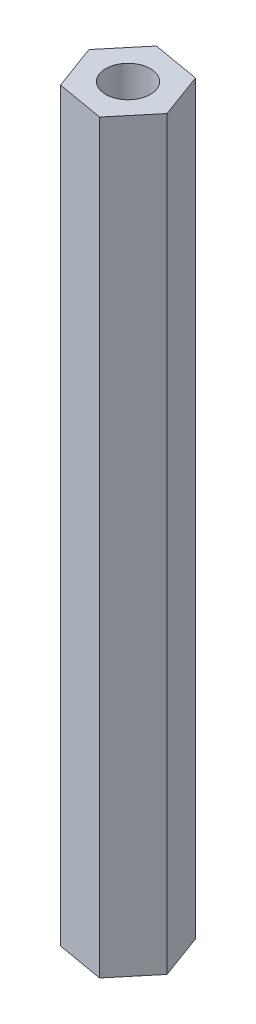
SolidWorks part; units mm, degrees
ref_plane "Front Plane" through (0, 0, 0) normal (0, 0, 1) x (1, 0, 0)
ref_plane "Top Plane" through (0, 0, 0) normal (0, 1, 0) x (1, 0, 0)
ref_plane "Right Plane" through (0, 0, 0) normal (1, 0, 0) x (0, 0, -1)
sketch "Sketch1" plane through (0, 0, 0) normal (0, 1, 0) x (1, 0, 0)
  line L0 (1.1114, -3.016) -> (3.1677, -0.5455)
  line L1 (3.1677, -0.5455) -> (2.0562, 2.4705)
  line L2 (2.0562, 2.4705) -> (-1.1114, 3.016)
  line L3 (-1.1114, 3.016) -> (-3.1677, 0.5455)
  line L4 (-3.1677, 0.5455) -> (-2.0562, -2.4705)
  line L5 (-2.0562, -2.4705) -> (1.1114, -3.016)
  circle A0 centre (0, 0) radius 1.5
  dimension "D1" = 3
  dimension "D2" = 5.5673
  dimension "D3" = 240
  dimension "D4" = 240
  dimension "D5" = 240
extrude "Boss-Extrude1" add sketch "Sketch1" along normal blind 50
